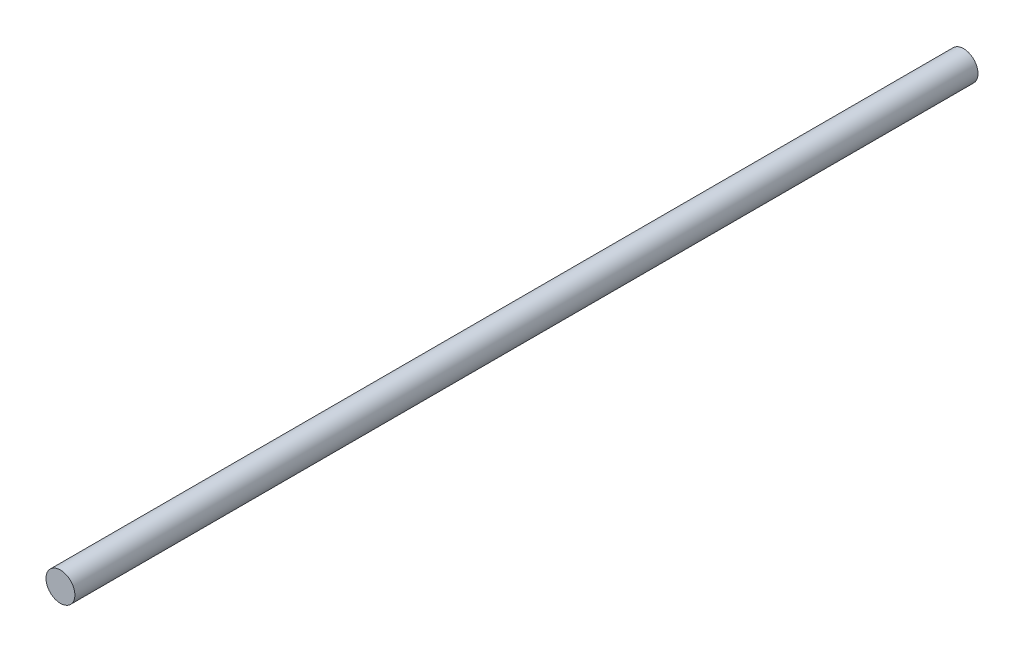
SolidWorks part; units mm, degrees
material "AISI 1020"
ref_plane "Alzado" through (0, 0, 0) normal (0, 0, 1) x (1, 0, 0)
ref_plane "Planta" through (0, 0, 0) normal (0, 1, 0) x (1, 0, 0)
ref_plane "Vista lateral" through (0, 0, 0) normal (1, 0, 0) x (0, 0, -1)
sketch "Croquis1" plane through (0, 0, 0) normal (0, 0, 1) x (1, 0, 0)
  circle A0 centre (0, 0) radius 4
  dimension "D1" = 8
extrude "Saliente-Extruir1" add sketch "Croquis1" along normal blind 250
